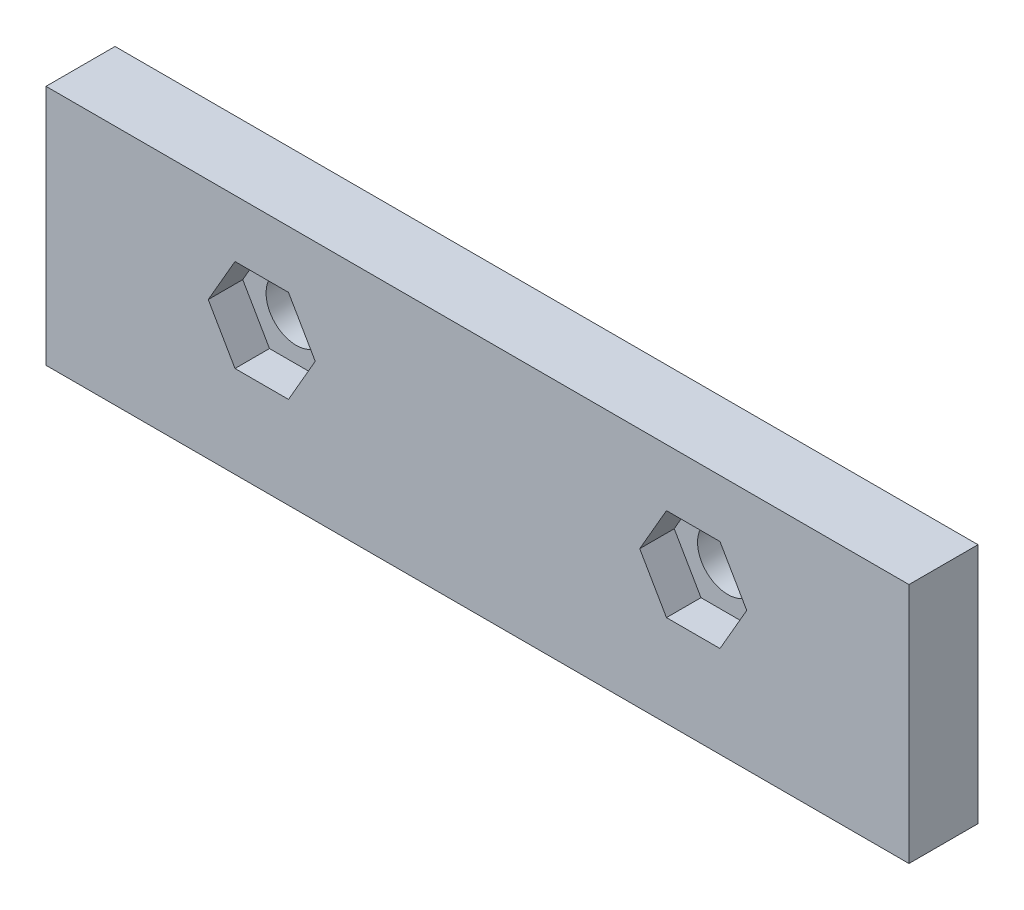
SolidWorks part; units mm, degrees
ref_plane "Front Plane" through (0, 0, 0) normal (0, 0, 1) x (1, 0, 0)
ref_plane "Top Plane" through (0, 0, 0) normal (0, 1, 0) x (1, 0, 0)
ref_plane "Right Plane" through (0, 0, 0) normal (1, 0, 0) x (0, 0, -1)
sketch "Sketch1" plane through (0, 0, 0) normal (0, 0, 1) x (1, 0, 0)
  line L1 (0, 0) -> (50, 0)
  line L2 (0, 0) -> (0, 14)
  line L3 (0, 14) -> (50, 14)
  line L4 (50, 0) -> (50, 14)
  circle A0 centre (12.5, 8) radius 1.75
  circle A1 centre (37.5, 8) radius 1.75
  dimension "D3" = 3.5
  dimension "D1" = 14
  dimension "D2" = 50
  dimension "D4" = 12.5
  dimension "D5" = 25
  dimension "D6" = 12.5
  dimension "D7" = 6
extrude "Boss-Extrude1" add sketch "Sketch1" along normal blind 4
sketch "NutHoleSketch7" plane through (0, 0, 4) normal (0, 0, 1) x (1, 0, 0)
  line L1 (14.05, 5.3153) -> (15.6, 8)
  line L2 (15.6, 8) -> (14.05, 10.6847)
  line L3 (14.05, 10.6847) -> (10.95, 10.6847)
  line L4 (10.95, 10.6847) -> (9.4, 8)
  line L5 (9.4, 8) -> (10.95, 5.3153)
  line L6 (10.95, 5.3153) -> (14.05, 5.3153)
  line L7 (39.05, 5.3153) -> (40.6, 8)
  line L8 (40.6, 8) -> (39.05, 10.6847)
  line L9 (39.05, 10.6847) -> (35.95, 10.6847)
  line L10 (35.95, 10.6847) -> (34.4, 8)
  line L11 (34.4, 8) -> (35.95, 5.3153)
  line L12 (35.95, 5.3153) -> (39.05, 5.3153)
  circle A0 centre (12.5, 8) radius 2.6847 construction
  circle A1 centre (37.5, 8) radius 2.6847 construction
  dimension "D1" = 6.2
extrude "NutHoleCut-Extrude1" cut sketch "NutHoleSketch7" against normal blind 2
equation "\"LinearRailHoleDistance\"= 25mm'Spec"
equation "\"D5@Sketch1\"=\"LinearRailHoleDistance\""
equation "\"D2@Sketch1\"=\"LinearRailHoleDistance\" * 2"
equation "\"D4@Sketch1\"=\"LinearRailHoleDistance\"/2"
equation "\"LinearRailHoleDiameter\"= 3.5mm'Spec"
equation "\"D3@Sketch1\"=\"LinearRailHoleDiameter\""
equation "\"LinearRailHeight\"= 8mm'Spec"
equation "\"LinearRailWidth\"= 12mm'Spec"
equation "\"D1@Sketch1\"=\"LinearRailWidth\"+2mm"
equation "\"D1@Boss-Extrude1\"=\"ConnectingPlateHeight\""
equation "\"D7@Sketch1\"=\"LinearRailWidth\"/2"
equation "\"ConnectingPlateHeight\"= \"LinearRailHeight\" / 2"
equation "\"D1@NutHoleCut-Extrude1\"=\"LinearRailSupportNutHoleDepth\""
equation "\"LinearRailSupportNutWidth\"= 6.2mm"
equation "\"D1@NutHoleSketch7\" = \"LinearRailSupportNutWidth\""
equation "\"LinearRailSupportNutHoleDepth\"= \"LinearRailHeight\" / 4"
